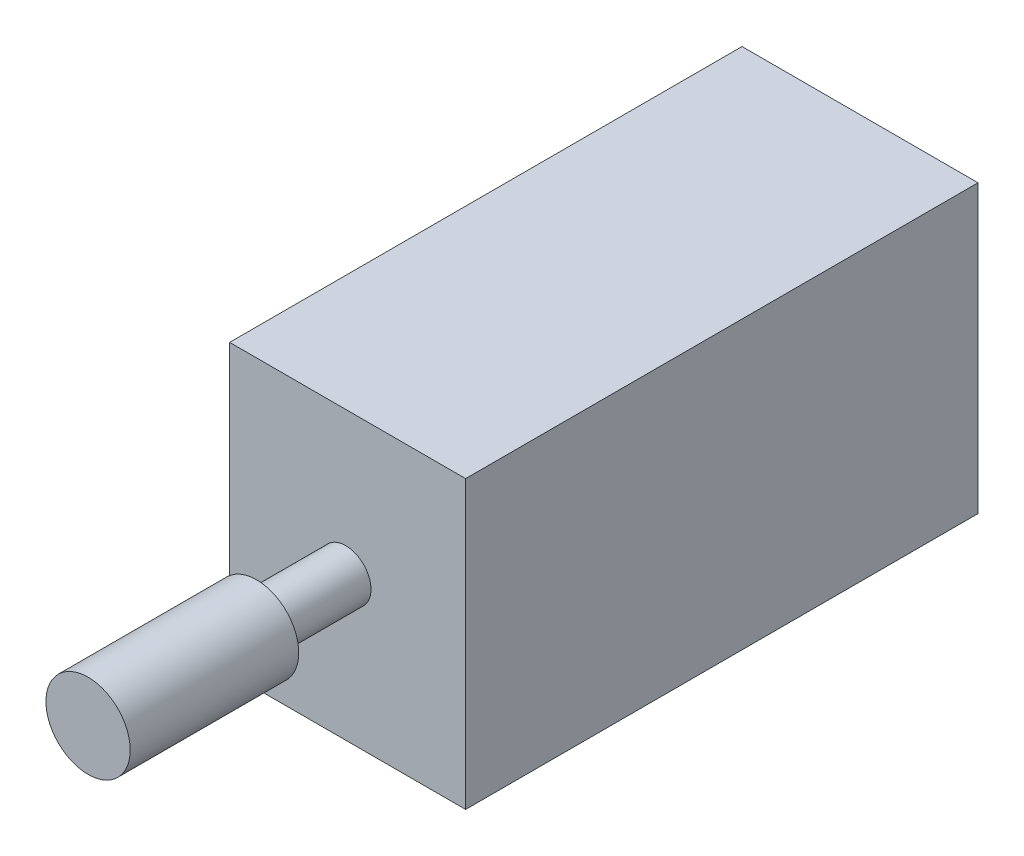
SolidWorks part; units mm, degrees
ref_plane "Front Plane" through (0, 0, 0) normal (0, 0, 1) x (1, 0, 0)
ref_plane "Top Plane" through (0, 0, 0) normal (0, 1, 0) x (1, 0, 0)
ref_plane "Right Plane" through (0, 0, 0) normal (1, 0, 0) x (0, 0, -1)
sketch "Sketch1" plane through (0, 0, 0) normal (1, 0, 0) x (0, 0, -1)
  line L1 (15.2, -8.5) -> (-15.2, -8.5)
  line L2 (15.2, -8.5) -> (15.2, 8.5)
  line L3 (15.2, 8.5) -> (-15.2, 8.5)
  line L4 (-15.2, -8.5) -> (-15.2, 8.5)
  line L5 (15.2, -8.5) -> (-15.2, 8.5) construction
  line L6 (15.2, 8.5) -> (-15.2, -8.5) construction
  point P0 (0, 0)
  dimension "D1" = 30.4
  dimension "D2" = 17
extrude "Boss-Extrude1" add sketch "Sketch1" along normal blind 14
sketch "Sketch2" plane through (0, 0, 15.2) normal (0, 0, 1) x (1, 0, 0)
  circle A0 centre (6.8871, 0) radius 1.5
  dimension "D1" = 3
extrude "Boss-Extrude2" add sketch "Sketch2" along normal blind 5.4
sketch "Sketch3" plane through (0, 0, 20.6) normal (0, 0, 1) x (1, 0, 0)
  line L0 (14, -8.5) -> (0, -8.5) construction
  circle A0 centre (7, 0) radius 2.5
  point P2 (0, 0)
  point P4 (0, 0)
  point P7 (7, -8.5)
  dimension "D1" = 5
extrude "Boss-Extrude3" add sketch "Sketch3" along normal blind 10
sketch "Sketch4" plane through (0, 0, 30.6) normal (0, 0, 1) x (1, 0, 0)
  circle A0 centre (7, 0) radius 2.5
  circle A1 centre (7, 0) radius 2.5 construction
  point P2 (7, -0.5305)
